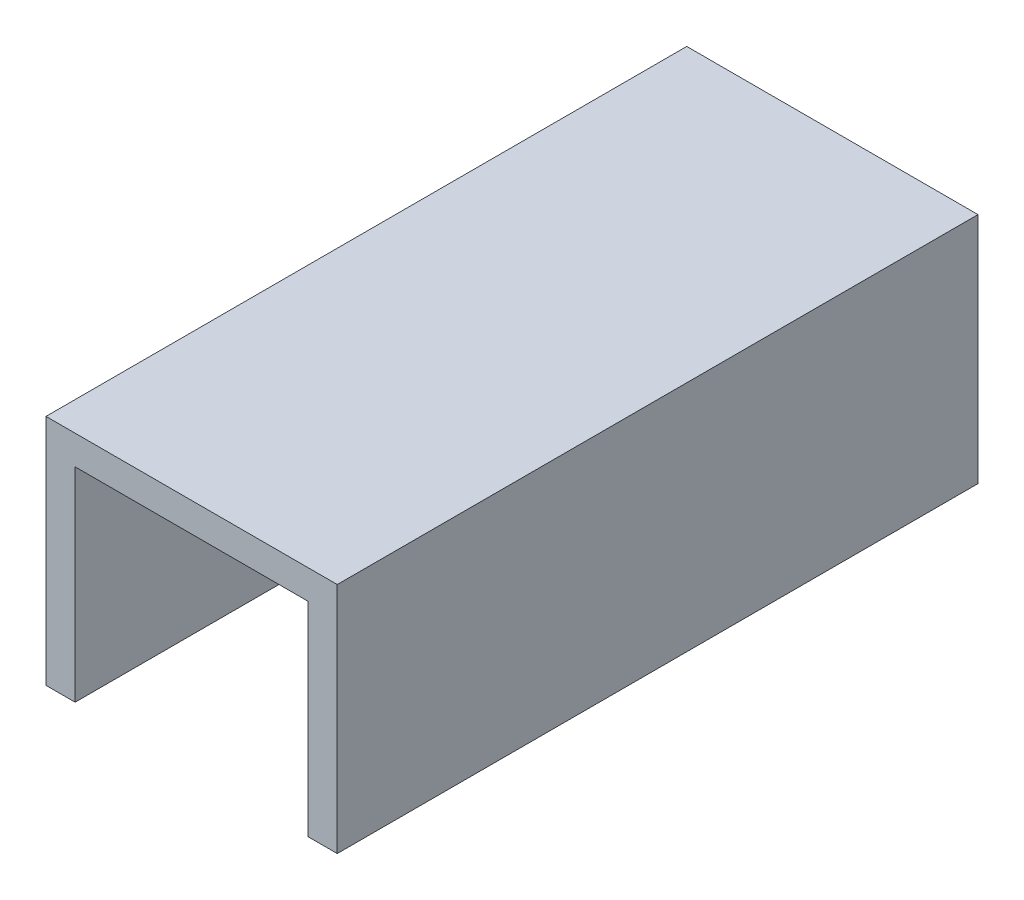
SolidWorks part; units mm, degrees
ref_plane "Front Plane" through (0, 0, 0) normal (0, 0, 1) x (1, 0, 0)
ref_plane "Top Plane" through (0, 0, 0) normal (0, 1, 0) x (1, 0, 0)
ref_plane "Right Plane" through (0, 0, 0) normal (1, 0, 0) x (0, 0, -1)
sketch "Sketch1" plane through (0, 0, 0) normal (0, 0, 1) x (1, 0, 0)
  line L1 (-25, 20) -> (25, 20)
  line L2 (-25, 20) -> (-25, -20)
  line L3 (-25, -20) -> (25, -20)
  line L4 (25, 20) -> (25, -20)
  line L5 (-25, 20) -> (25, -20) construction
  line L6 (-25, -20) -> (25, 20) construction
  point P0 (0, 0)
  dimension "D1" = 50
  dimension "D2" = 40
extrude "Boss-Extrude1" add sketch "Sketch1" along normal blind 110
sketch "Sketch2" plane through (0, 0, 110) normal (0, 0, 1) x (1, 0, 0)
  line L0 (-20, -20) -> (20, -20)
  line L1 (-20, -20) -> (-20, 15)
  line L2 (20, -20) -> (20, 15)
  line L3 (-20, 15) -> (20, 15)
  line L4 (-25, -20) -> (25, -20) construction
  line L5 (-25, 20) -> (-25, -20) construction
  line L6 (25, 20) -> (-25, 20) construction
  dimension "D1" = 40
  dimension "D2" = 5
  dimension "D3" = 5
extrude "Cut-Extrude1" cut sketch "Sketch2" against normal blind 105
